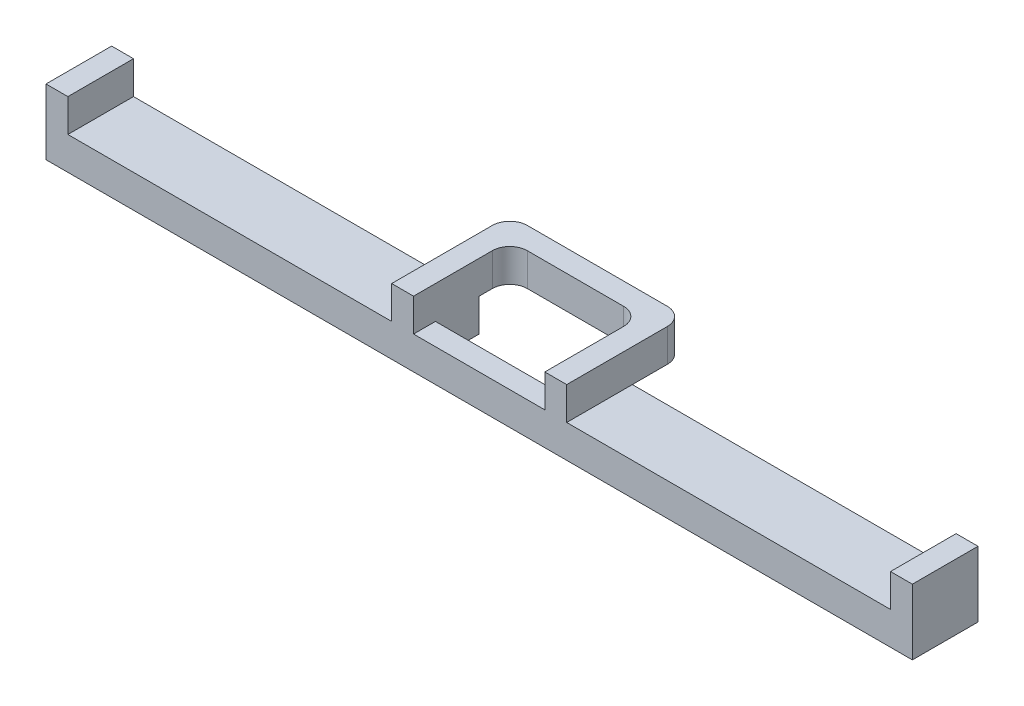
SolidWorks part; units mm, degrees
material "ABS"
ref_plane "前视基准面" through (0, 0, 0) normal (0, 0, 1) x (1, 0, 0)
ref_plane "上视基准面" through (0, 0, 0) normal (0, 1, 0) x (1, 0, 0)
ref_plane "右视基准面" through (0, 0, 0) normal (1, 0, 0) x (0, 0, -1)
sketch "草图1" plane through (0, 0, 0) normal (0, 0, 1) x (1, 0, 0)
  line L0 (-94, 7.5) -> (-99, 7.5)
  line L1 (99, 7.5) -> (94, 7.5)
  line L2 (99, 7.5) -> (99, -7.5)
  line L3 (99, -7.5) -> (-99, -7.5)
  line L4 (-99, 7.5) -> (-99, -7.5)
  line L5 (99, 7.5) -> (-99, -7.5) construction
  line L6 (99, -7.5) -> (-99, 7.5) construction
  line L8 (-94, 7.5) -> (-94, 0)
  line L9 (-94, 0) -> (94, 0)
  line L10 (94, 7.5) -> (94, 0)
  point P0 (0, 0)
  dimension "D1" = 198
  dimension "D2" = 188
  dimension "D3" = 15
extrude "凸台-拉伸1" add sketch "草图1" along normal blind 15
sketch "草图2" plane through (0, 0, 15) normal (0, 0, 1) x (1, 0, 0)
  line L1 (20, -7.5) -> (-20, -7.5)
  line L2 (20, -7.5) -> (20, 7.5)
  line L3 (20, 7.5) -> (15, 7.5)
  line L4 (-20, -7.5) -> (-20, 7.5)
  line L5 (20, -7.5) -> (-20, 7.5) construction
  line L6 (20, 7.5) -> (-20, -7.5) construction
  line L7 (99, 7.5) -> (94, 7.5) construction
  line L8 (94, 0) -> (-94, 0) construction
  line L10 (-15, 7.5) -> (-15, 0)
  line L11 (-15, 0) -> (15, 0)
  line L12 (15, 7.5) -> (15, 0)
  line L13 (-15, 7.5) -> (-20, 7.5)
  point P0 (0, 0)
  dimension "D1" = 40
  dimension "D2" = 5
extrude "凸台-拉伸2" add sketch "草图2" against normal up to surface (15 mm away) up to face at (0, 1.875, 0)
sketch "草图3" plane through (0, 0, 0) normal (0, 1, 0) x (1, 0, 0)
  line L1 (-15, 0) -> (15, 0)
  line L2 (-15, 0) -> (-15, -10)
  line L3 (-15, -10) -> (15, -10)
  line L4 (15, 0) -> (15, -10)
  line L5 (15, -15) -> (-15, -15) construction
  point P7 (0, 0)
  point P8 (0, 0)
  point P9 (0, 0)
  dimension "D1" = 5
extrude "切除-拉伸1" cut sketch "草图3" against normal through all both and the other way through all
sketch "草图4" plane through (0, 0, 0) normal (0, 1, 0) x (1, 0, 0)
  line L0 (-15, -11.1767) -> (-15, 3)
  line L1 (15, 0) -> (15, 3)
  line L2 (-15, 0) -> (-15, -15) construction
  line L3 (-11, 7) -> (11, 7)
  line L4 (-15, -11.1767) -> (-20, -11.1767)
  line L5 (-20, 0) -> (-20, -15) construction
  line L6 (-20, -11.1767) -> (-20, 8)
  line L7 (-16, 12) -> (16, 12)
  line L8 (20, 8) -> (20, 0)
  line L9 (20, 0) -> (15, 0)
  line L10 (15, -10) -> (-15, -10) construction
  arc A0 (15, 3) -> (11, 7) centre (11, 3) ccw
  arc A1 (-11, 7) -> (-15, 3) centre (-11, 3) ccw
  arc A2 (-16, 12) -> (-20, 8) centre (-16, 8) ccw
  arc A3 (16, 12) -> (20, 8) centre (16, 8) cw
  point P14 (20, 14.8193)
  dimension "D1" = 4
  dimension "D2" = 5
  dimension "D3" = 17
extrude "凸台-拉伸3" add sketch "草图4" along normal up to surface (7.5 mm away) up to face at (-17.5, 7.5, 7.5)
